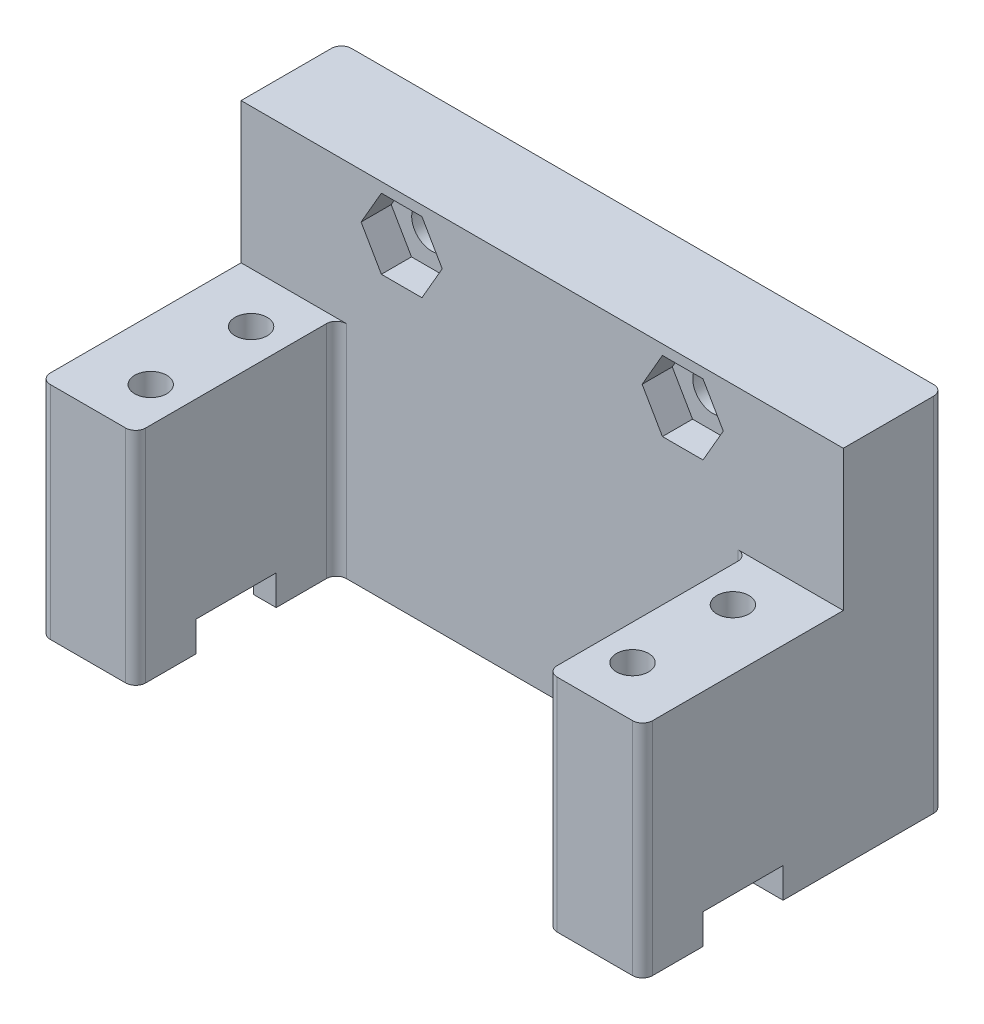
SolidWorks part; units mm, degrees
ref_plane "Front Plane" through (0, 0, 0) normal (0, 0, 1) x (1, 0, 0)
ref_plane "Top Plane" through (0, 0, 0) normal (0, 1, 0) x (1, 0, 0)
ref_plane "Right Plane" through (0, 0, 0) normal (1, 0, 0) x (0, 0, -1)
sketch "Sketch1" plane through (0, 0, 0) normal (0, 0, 1) x (1, 0, 0)
  line L0 (30, 0) -> (30, 10.1108) construction
  line L1 (0, 0) -> (60, 0)
  line L2 (0, 0) -> (0, -36)
  line L3 (0, -36) -> (60, -36)
  line L4 (60, 0) -> (60, -36)
  circle A0 centre (16, -4.5) radius 2
  circle A1 centre (44, -4.5) radius 2
  dimension "D3" = 4.5
  dimension "D6" = 4
  dimension "D1" = 60
  dimension "D2" = 36
  dimension "D4" = 14
  dimension "D7" = 28
  dimension "D5" = 2
extrude "Boss-Extrude1" add sketch "Sketch1" along normal blind 10
sketch "Sketch2" plane through (0, -36, 0) normal (0, -1, 0) x (1, 0, 0)
  line L1 (0, 10) -> (9.5, 10)
  line L2 (0, 10) -> (0, 30)
  line L3 (0, 30) -> (9.5, 30)
  line L4 (9.5, 10) -> (9.5, 30)
  line L5 (60, 10) -> (50.5, 10)
  line L6 (60, 10) -> (60, 30)
  line L7 (60, 30) -> (50.5, 30)
  line L8 (50.5, 10) -> (50.5, 30)
  dimension "D1" = 41
  dimension "D2" = 9.5
  dimension "D3" = 20
  dimension "D4" = 20
extrude "Boss-Extrude2" add sketch "Sketch2" against normal blind 22
sketch "Sketch3" plane through (0, -14, 0) normal (0, 1, 0) x (1, 0, 0)
  line L0 (60, -10) -> (0, -10) construction
  line L1 (0, -30) -> (0, -10) construction
  circle A0 centre (6, -15) radius 1.6
  circle A1 centre (54, -15) radius 1.6
  circle A2 centre (54, -25) radius 1.6
  circle A3 centre (6, -25) radius 1.6
  dimension "D1" = 2
  dimension "D5" = 3.2
  dimension "D3" = 5
  dimension "D4" = 6
  dimension "D2" = 2
extrude "Cut-Extrude1" cut sketch "Sketch3" against normal up to next
sketch "Sketch4" plane through (0, 0, 10) normal (0, 0, 1) x (1, 0, 0)
  line L0 (30, 0) -> (30, 11.4908) construction
  line L1 (13.9793, -1) -> (11.9585, -4.5)
  line L2 (11.9585, -4.5) -> (13.9793, -8)
  line L3 (13.9793, -8) -> (18.0207, -8)
  line L4 (18.0207, -8) -> (20.0415, -4.5)
  line L5 (20.0415, -4.5) -> (18.0207, -1)
  line L6 (18.0207, -1) -> (13.9793, -1)
  line L7 (60, 0) -> (0, 0) construction
  circle A0 centre (16, -4.5) radius 3.5 construction
  dimension "D1" = 7
extrude "Cut-Extrude2" cut sketch "Sketch4" against normal blind 3
pattern_linear "LPattern1" count 2 spacing 28 along (1, 0, 0) of "Cut-Extrude2"
fillet "Fillet1" radius 1 8 edges at (50.5, -25, 30) (60, -25, 30) (9.5, -25, 30) (0, -25, 30) (50.5, -25, 10) (9.5, -25, 10) (0, -18, 0) (60, -18, 0)
sketch "Sketch5" plane through (0, 0, 0) normal (0, 1, 0) x (1, 0, 0)
  line L0 (30, 0) -> (30, -17.5)
  line L1 (59, 0) -> (1, 0) construction
  line L2 (30, -17.5) -> (37.5, -17.5)
  line L3 (30, 0) -> (30, 16)
  line L4 (30, 16) -> (37.5, -17.5)
sketch "Sketch6" plane through (60, 0, 0) normal (1, 0, 0) x (0, 0, -1)
  line L0 (-20, -14) -> (-20, -36)
  line L2 (-29, -36) -> (-1, -36) construction
  line L4 (-24, -33) -> (-16, -33)
  line L5 (-24, -33) -> (-24, -36)
  line L6 (-24, -36) -> (-16, -36)
  line L7 (-16, -33) -> (-16, -36)
  line L8 (-24, -33) -> (-16, -36) construction
  line L9 (-24, -36) -> (-16, -33) construction
  point P6 (-20, -34.5)
  dimension "D1" = 8
  dimension "D2" = 3
  dimension "D3" = 10
extrude "Cut-Extrude3" cut sketch "Sketch6" against normal through all contours L5 L6 L7 L4
